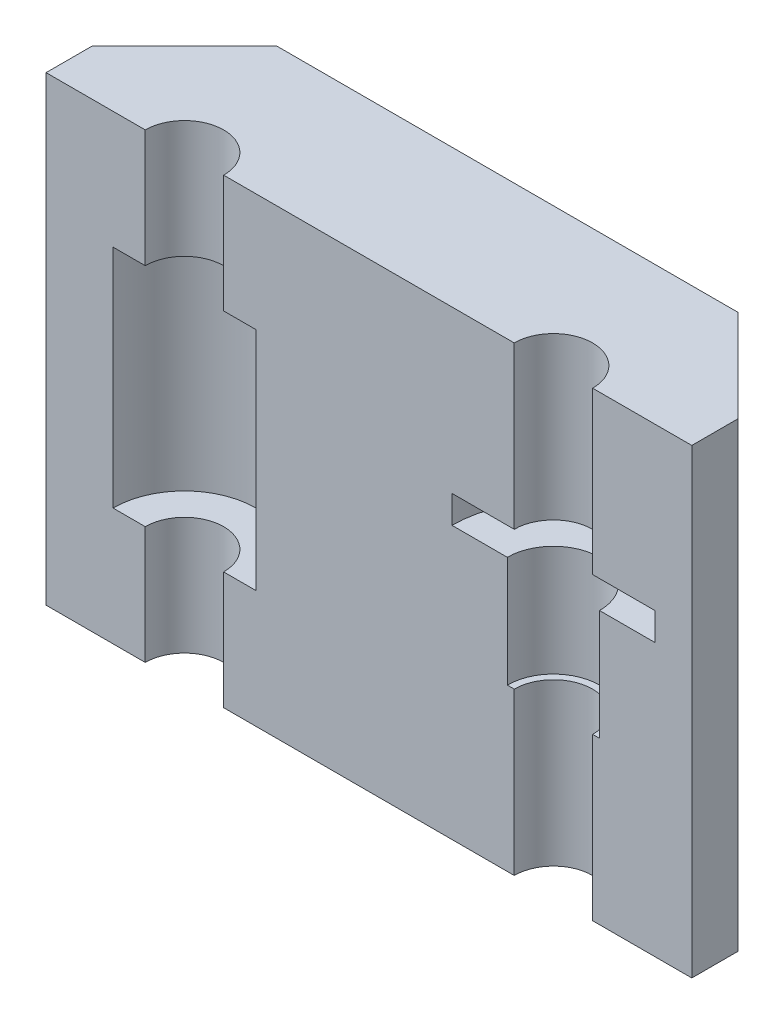
SolidWorks part; units mm, degrees
ref_plane "Plan de face" through (0, 0, 0) normal (0, 0, 1) x (1, 0, 0)
ref_plane "Plan de dessus" through (0, 0, 0) normal (0, 1, 0) x (1, 0, 0)
ref_plane "Plan de droite" through (0, 0, 0) normal (1, 0, 0) x (0, 0, -1)
sketch "Esquisse1" plane through (0, 0, 0) normal (0, 0, 1) x (1, 0, 0)
  line L1 (-35, -25) -> (35, -25)
  line L2 (-35, -25) -> (-35, 25)
  line L3 (-35, 25) -> (35, 25)
  line L4 (35, -25) -> (35, 25)
  line L5 (-35, -25) -> (35, 25) construction
  line L6 (-35, 25) -> (35, -25) construction
  point P0 (0, 0)
  dimension "D1" = 70
  dimension "D2" = 50
extrude "Boss.-Extru.1" add sketch "Esquisse1" along normal blind 15
sketch "Esquisse2" plane through (0, 25, 0) normal (0, 1, 0) x (1, 0, 0)
  line L0 (35, -15) -> (-35, -15) construction
  line L1 (-35, -15) -> (-35, 0) construction
  line L2 (35, -15) -> (35, 0) construction
  circle A0 centre (-20, -15) radius 4.25
  circle A1 centre (20, -15) radius 4.25
  dimension "D1" = 8.5
  dimension "D3" = 8.5
  dimension "D2" = 15
  dimension "D4" = 15
extrude "Enlèv. mat.-Extru.1" cut sketch "Esquisse2" against normal through all
ref_plane "Plan2" through (0, 7.5, 0) normal (0, 1, 0) x (1, 0, 0)
sketch "Esquisse3" plane through (0, 0, 0) normal (0, 1, 0) x (1, 0, 0)
  circle A0 centre (-20, -15) radius 7.75
  dimension "D1" = 15.5
extrude "Enlèv. mat.-Extru.2" cut sketch "Esquisse3" against normal blind 12.25 and the other way blind 12.25
sketch "Esquisse4" plane through (0, 7.5, 0) normal (0, 1, 0) x (1, 0, 0)
  circle A0 centre (20, -15) radius 11
  dimension "D1" = 22
extrude "Enlèv. mat.-Extru.3" cut sketch "Esquisse4" against normal blind 3
sketch "Esquisse5" plane through (0, 7.5, 0) normal (0, 1, 0) x (1, 0, 0)
  circle A0 centre (20, -15) radius 5
  dimension "D1" = 10
extrude "Enlèv. mat.-Extru.4" cut sketch "Esquisse5" against normal blind 15
chamfer "Chanfrein1" distance 10 angle 45 2 edges at (35, 0, 0) (-35, 0, 0)
